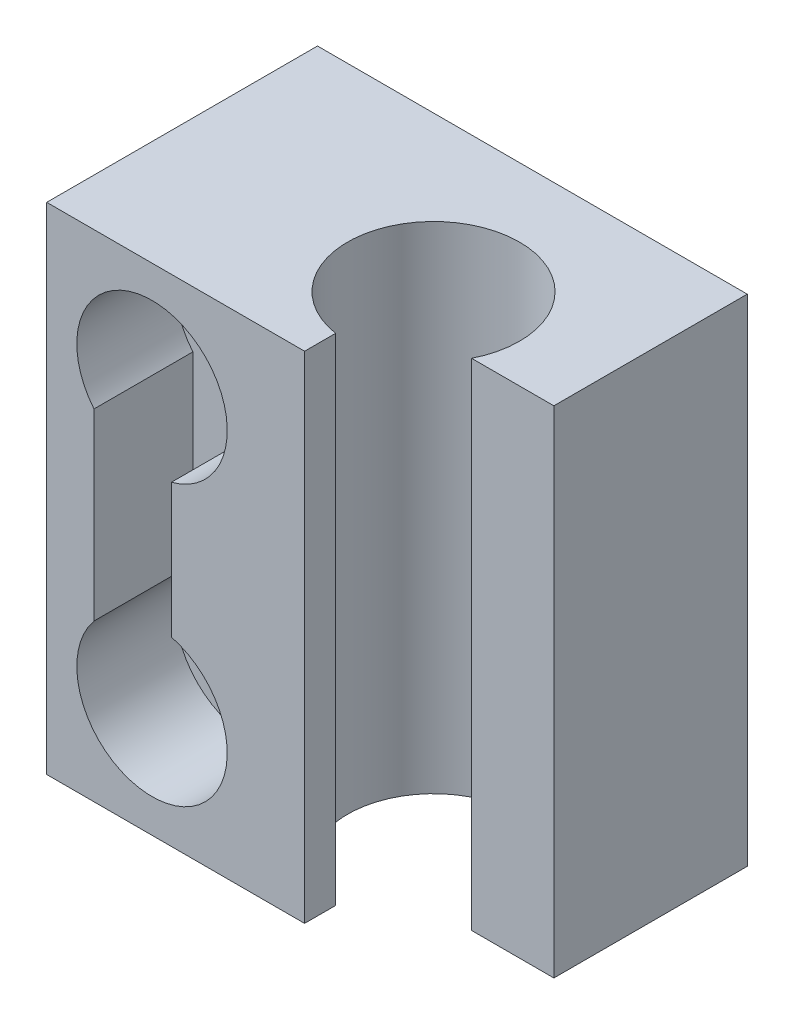
SolidWorks part; units mm, degrees
ref_plane "Front Plane" through (0, 0, 0) normal (0, 0, 1) x (1, 0, 0)
ref_plane "Top Plane" through (0, 0, 0) normal (0, 1, 0) x (1, 0, 0)
ref_plane "Right Plane" through (0, 0, 0) normal (1, 0, 0) x (0, 0, -1)
sketch "Sketch1" plane through (0, 0, 0) normal (0, 0, 1) x (1, 0, 0)
  line L1 (-47.3282, -29.616) -> (-72.7282, -29.616)
  line L2 (-47.3282, -29.616) -> (-47.3282, -0.3298)
  line L3 (-47.3282, -0.3298) -> (-72.7282, -0.3298)
  line L4 (-72.7282, -29.616) -> (-72.7282, -0.3298)
  dimension "D1" = 25.4
  dimension "D2" = 29.2862
extrude "Boss-Extrude1" add sketch "Sketch1" along normal blind 16.002
sketch "Sketch2" plane through (0, 0, 16.002) normal (0, 0, 1) x (1, 0, 0)
  line L0 (-69.9342, -9.5082) -> (-69.9342, -20.3614)
  line L1 (-65.3622, -10.9753) -> (-65.3622, -18.8942)
  line L3 (-47.3282, -0.3298) -> (-72.7282, -0.3298) construction
  line L5 (-72.7282, -0.3298) -> (-72.7282, -29.616) construction
  arc A0 (-65.3622, -10.9753) -> (-69.9342, -9.5082) centre (-66.5052, -6.6798) ccw
  arc A1 (-69.9342, -20.3614) -> (-65.3622, -18.8942) centre (-66.5052, -23.1898) ccw
  dimension "D1" = 1.778
  dimension "D2" = 25.4
  dimension "D3" = 8.89
  dimension "D4" = 1.905
  dimension "D5" = 2.794
  dimension "D6" = 4.572
extrude "Cut-Extrude1" cut sketch "Sketch2" against normal blind 5.842
sketch "Sketch3" plane through (0, 0, 10.16) normal (0, 0, 1) x (1, 0, 0)
  circle A0 centre (-66.5052, -6.6798) radius 1.905
  circle A1 centre (-66.5052, -23.1898) radius 1.905
  dimension "D1" = 3.81
  dimension "D2" = 3.81
extrude "Cut-Extrude2" cut sketch "Sketch3" against normal through all
sketch "Sketch4" plane through (0, -0.3298, 0) normal (0, 1, 0) x (1, 0, 0)
  line L0 (-47.3282, -16.002) -> (-47.3282, 0) construction
  line L1 (-47.3282, -16.002) -> (-72.7282, -16.002) construction
  line L2 (-57.4882, -16.002) -> (-57.4882, -14.1665)
  line L3 (-47.3282, -11.43) -> (-52.1896, -11.43)
  line L4 (-47.3282, -16.002) -> (-47.3282, -11.43)
  line L5 (-47.3282, -16.002) -> (-57.4882, -16.002)
  line L6 (-72.7282, -16.002) -> (-72.7282, 0) construction
  line L7 (-47.3282, 0) -> (-72.7282, 0) construction
  arc A0 (-52.1896, -11.43) -> (-57.4882, -14.1665) centre (-56.7262, -9.144) ccw
  dimension "D1" = 9.398
  dimension "D2" = 6.858
  dimension "D3" = 10.16
  dimension "D4" = 15.24
  dimension "D5" = 11.43
extrude "Cut-Extrude3" cut sketch "Sketch4" against normal through all
